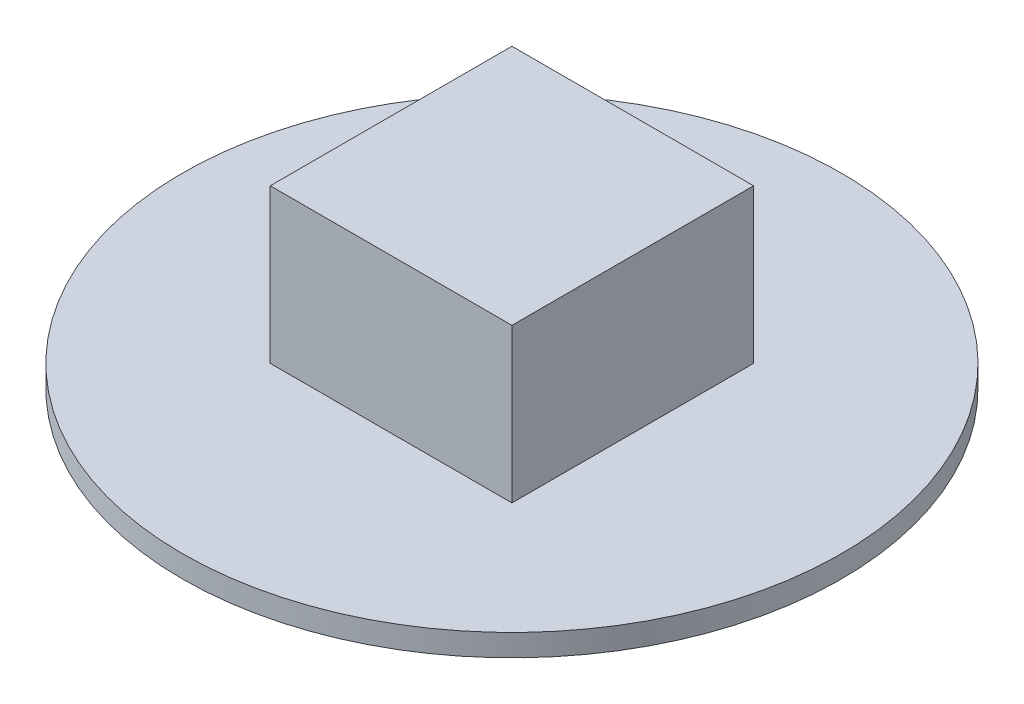
SolidWorks part; units mm, degrees
ref_plane "前视基准面" through (0, 0, 0) normal (0, 0, 1) x (1, 0, 0)
ref_plane "上视基准面" through (0, 0, 0) normal (0, 1, 0) x (1, 0, 0)
ref_plane "右视基准面" through (0, 0, 0) normal (1, 0, 0) x (0, 0, -1)
other "Configuration Table"
sketch "草图1" plane through (0, 0, 0) normal (0, 1, 0) x (1, 0, 0)
  circle A0 centre (0, 0) radius 150
  point P13 (0, 0)
  dimension "D1" = 300
extrude "凸台-拉伸2" add sketch "草图1" along normal blind 10
sketch "草图2" plane through (0, 10, 0) normal (0, 1, 0) x (1, 0, 0)
  line L1 (-55, 55) -> (55, 55)
  line L2 (-55, 55) -> (-55, -55)
  line L3 (-55, -55) -> (55, -55)
  line L4 (55, 55) -> (55, -55)
  line L5 (-55, 55) -> (55, -55) construction
  line L6 (-55, -55) -> (55, 55) construction
  point P0 (0, 0)
  dimension "D1" = 110
  dimension "D2" = 110
extrude "凸台-拉伸3" add sketch "草图2" along normal blind 70
sketch "草图3" plane through (0, 0, 0) normal (0, -1, 0) x (1, 0, 0)
  line L0 (0, 0) -> (100, 0) construction
  line L1 (0, 0) -> (50, -86.6025) construction
  circle A0 centre (0, 0) radius 100 construction
  circle A1 centre (50, -86.6025) radius 25
  circle A2 centre (-100, 0) radius 25
  circle A3 centre (50, 86.6025) radius 25
  point P13 (0, 0)
  dimension "D1" = 200
  dimension "D3" = 50
  dimension "D2" = 60
  dimension "D4" = 3
sketch "草图4" plane through (0, 0, 0) normal (0, -1, 0) x (1, 0, 0)
  circle A0 centre (0, 0) radius 100 construction
  circle A1 centre (-100, 0) radius 25
  circle A2 centre (50, 86.6025) radius 25
  circle A3 centre (50, -86.6025) radius 25
  point P11 (0, 0)
  dimension "D1" = 200
  dimension "D2" = 50
  dimension "D3" = 3
